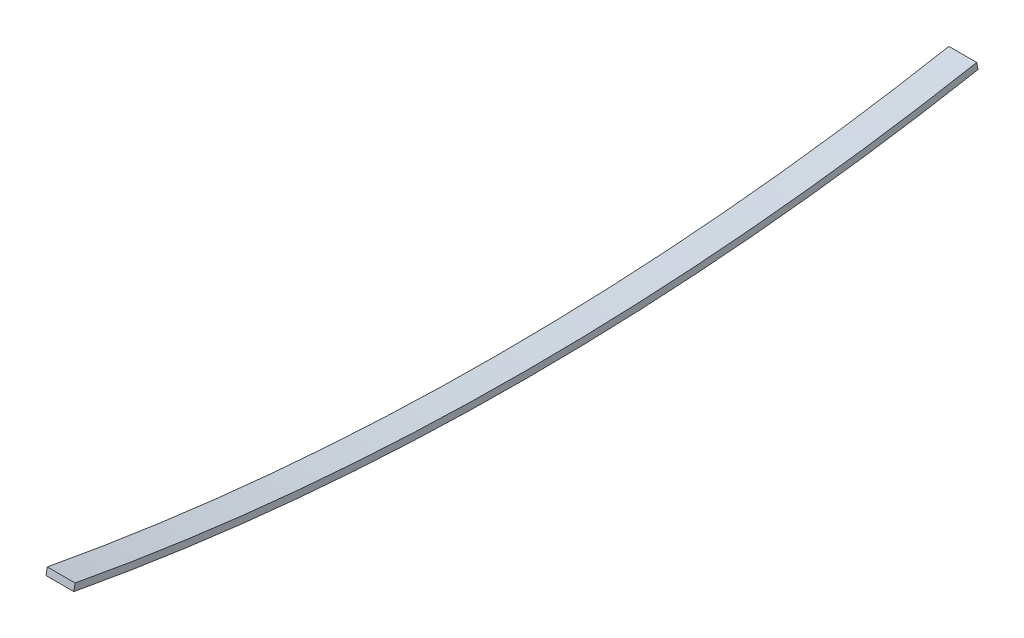
SolidWorks part; units mm, degrees
ref_plane "Front Plane" through (0, 0, 0) normal (0, 0, 1) x (1, 0, 0)
ref_plane "Top Plane" through (0, 0, 0) normal (0, 1, 0) x (1, 0, 0)
ref_plane "Right Plane" through (0, 0, 0) normal (1, 0, 0) x (0, 0, -1)
sketch "Sketch1" plane through (0, 0, 0) normal (1, 0, 0) x (0, 0, -1)
  line L1 (32.5, -1.5) -> (-32.5, -1.5) construction
  line L2 (32.5, -1.5) -> (32.5, 1.5) construction
  line L3 (32.5, 1.5) -> (-32.5, 1.5) construction
  line L4 (-32.5, -1.5) -> (-32.5, 1.5) construction
  line L5 (32.5, -1.5) -> (-32.5, 1.5) construction
  line L6 (32.5, 1.5) -> (-32.5, -1.5) construction
  arc A0 (-32.5, 1.5) -> (32.5, 1.5) centre (0, 176.0417) ccw
  point P0 (0, 0)
  dimension "D1" = 65
  dimension "D2" = 3
extrude "Extrude-Thin1" add sketch "Sketch1" along normal blind 2 thin thin type one direction reverse wall 0.5
